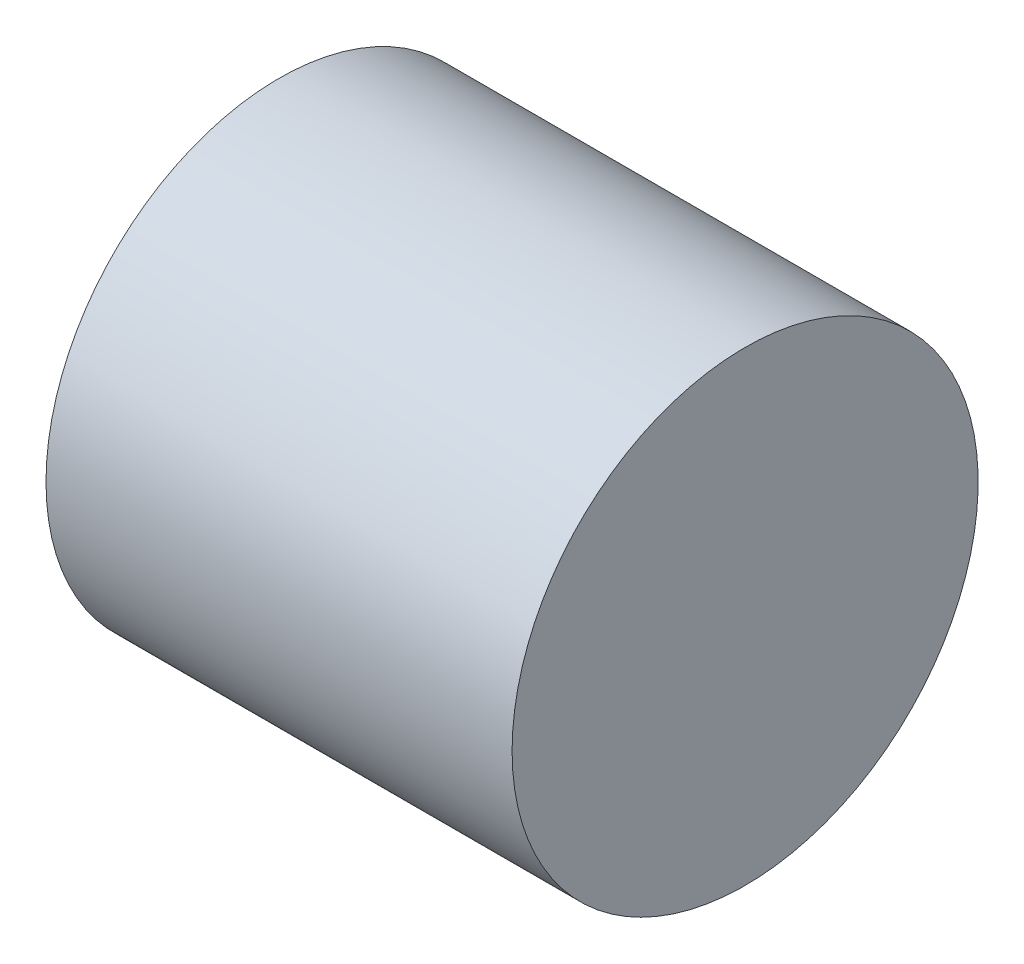
SolidWorks part; units mm, degrees
ref_plane "Plano frontal" through (0, 0, 0) normal (0, 0, 1) x (1, 0, 0)
ref_plane "Plano superior" through (0, 0, 0) normal (0, 1, 0) x (1, 0, 0)
ref_plane "Plano direito" through (0, 0, 0) normal (1, 0, 0) x (0, 0, -1)
sketch "Esboço2" plane through (0, 0, 0) normal (1, 0, 0) x (0, 0, -1)
  circle A0 centre (0, 0) radius 45
  dimension "D1" = 90
extrude "Ressalto-extrusão2" add sketch "Esboço2" along normal mid plane 90
